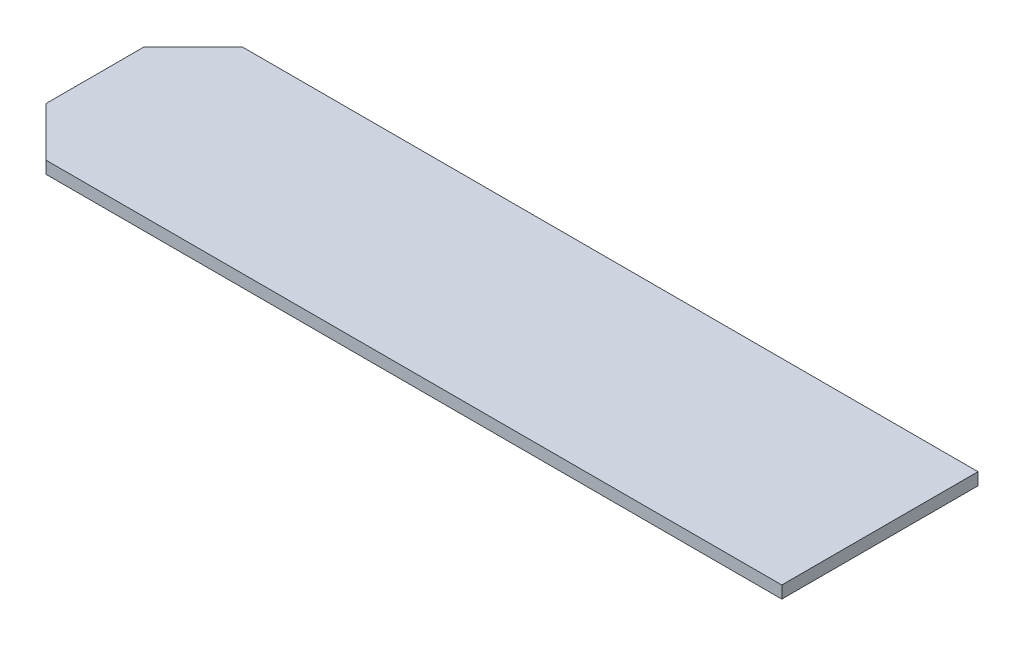
SolidWorks part; units mm, degrees
ref_plane "Front Plane" through (0, 0, 0) normal (0, 0, 1) x (1, 0, 0)
ref_plane "Top Plane" through (0, 0, 0) normal (0, 1, 0) x (1, 0, 0)
ref_plane "Right Plane" through (0, 0, 0) normal (1, 0, 0) x (0, 0, -1)
sketch "Sketch1" plane through (0, 0, 0) normal (0, 1, 0) x (1, 0, 0)
  line L1 (0, 0) -> (-203.2, 0)
  line L2 (0, 0) -> (0, 50.8)
  line L3 (0, 50.8) -> (-203.2, 50.8)
  line L4 (-203.2, 0) -> (-203.2, 50.8)
  dimension "D1" = 203.2
  dimension "D2" = 50.8
extrude "Boss-Extrude1" add sketch "Sketch1" along normal blind 3.175
chamfer "Chamfer1" distance 12.7 angle 45 2 edges at (-203.2, 1.5875, -50.8) (-203.2, 1.5875, 0)
